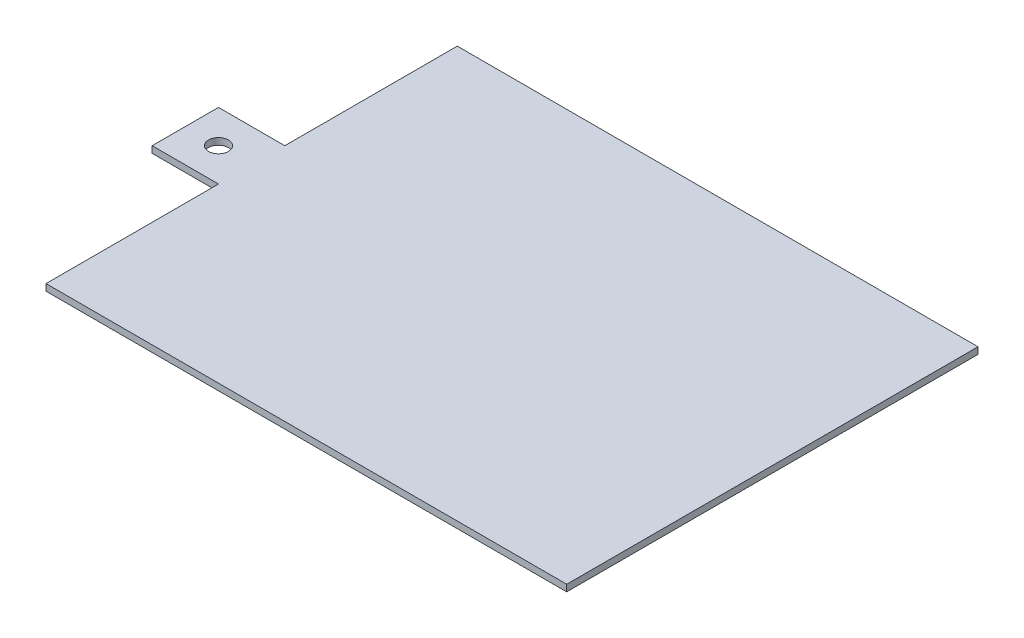
SolidWorks part; units mm, degrees
ref_plane "正面" through (0, 0, 0) normal (0, 0, 1) x (1, 0, 0)
ref_plane "平面" through (0, 0, 0) normal (0, 1, 0) x (1, 0, 0)
ref_plane "右側面" through (0, 0, 0) normal (1, 0, 0) x (0, 0, -1)
sketch "ｽｹｯﾁ1" plane through (0, 0, 0) normal (0, 1, 0) x (1, 0, 0)
  line L0 (-101, 0) -> (88.5, 0) construction
  line L1 (-68.5, 62) -> (88.5, 62)
  line L2 (-88.5, 10) -> (-88.5, -10)
  line L3 (-68.5, -62) -> (88.5, -62)
  line L4 (88.5, 62) -> (88.5, -62)
  line L5 (-88.5, 62) -> (88.5, -62) construction
  line L6 (-88.5, -62) -> (88.5, 62) construction
  line L9 (-88.5, 10) -> (-68.5, 10)
  line L10 (-68.5, 62) -> (-68.5, 10)
  line L11 (-88.5, -10) -> (-68.5, -10)
  line L12 (-68.5, -62) -> (-68.5, -10)
  line L13 (-68.5, 62) -> (-88.5, 62) construction
  line L14 (-88.5, 62) -> (-88.5, 10) construction
  line L15 (-88.5, -10) -> (-88.5, -62) construction
  line L16 (-88.5, -62) -> (-68.5, -62) construction
  line L17 (-88.5, 10) -> (-68.5, -10) construction
  line L18 (-68.5, 10) -> (-88.5, -10) construction
  circle A1 centre (-78.5, 0) radius 3
  point P0 (0, 0)
  dimension "D5" = 6
  dimension "D1" = 177
  dimension "D2" = 124
  dimension "D3" = 20
  dimension "D4" = 20
extrude "ﾎﾞｽ - 押し出し1" add sketch "ｽｹｯﾁ1" along normal blind 2
